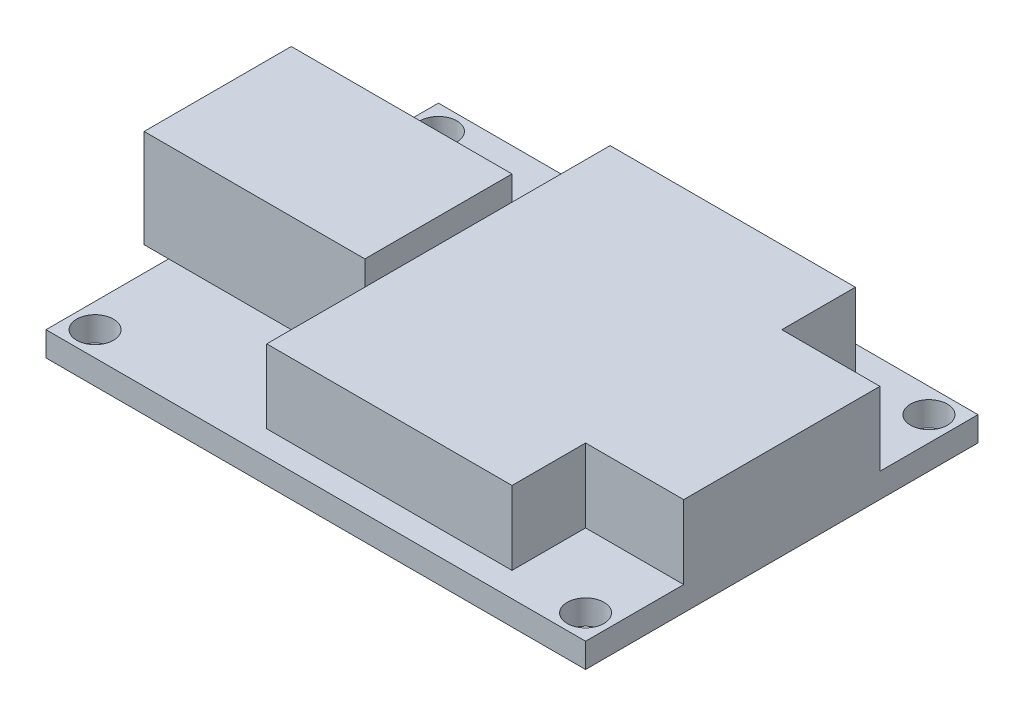
SolidWorks part; units mm, degrees
ref_plane "Front Plane" through (0, 0, 0) normal (0, 0, 1) x (1, 0, 0)
ref_plane "Top Plane" through (0, 0, 0) normal (0, 1, 0) x (1, 0, 0)
ref_plane "Right Plane" through (0, 0, 0) normal (1, 0, 0) x (0, 0, -1)
sketch "Sketch1" plane through (0, 0, 0) normal (0, 1, 0) x (1, 0, 0)
  line L1 (-17.4625, 12.7) -> (17.4625, 12.7)
  line L2 (-17.4625, 12.7) -> (-17.4625, -12.7)
  line L3 (-17.4625, -12.7) -> (17.4625, -12.7)
  line L4 (17.4625, 12.7) -> (17.4625, -12.7)
  line L5 (-17.4625, 12.7) -> (17.4625, -12.7) construction
  line L6 (-17.4625, -12.7) -> (17.4625, 12.7) construction
  point P0 (0, 0)
  dimension "D1" = 25.4
  dimension "D2" = 34.925
extrude "Boss-Extrude1" add sketch "Sketch1" along normal blind 1.5875
sketch "Sketch2" plane through (0, 1.5875, 0) normal (0, 1, 0) x (1, 0, 0)
  line L0 (17.4625, 12.7) -> (-17.4625, 12.7) construction
  line L1 (-4.7625, 11.1125) -> (11.1125, 11.1125)
  line L2 (-4.7625, 11.1125) -> (-4.7625, -11.1125)
  line L3 (-4.7625, -11.1125) -> (11.1125, -11.1125)
  line L4 (11.1125, 11.1125) -> (11.1125, 6.35)
  line L5 (-17.4625, -12.7) -> (17.4625, -12.7) construction
  line L6 (17.4625, -12.7) -> (17.4625, 12.7) construction
  line L7 (-17.4625, 12.7) -> (-17.4625, -12.7) construction
  line L8 (17.4625, 12.7) -> (-17.4625, 12.7) construction
  line L9 (11.1125, 6.35) -> (17.4625, 6.35)
  line L11 (11.1125, -6.35) -> (17.4625, -6.35)
  line L12 (17.4625, 6.35) -> (17.4625, -6.35)
  line L13 (11.1125, -6.35) -> (11.1125, -11.1125)
  dimension "D1" = 1.5875
  dimension "D2" = 1.5875
  dimension "D3" = 6.35
  dimension "D4" = 12.7
  dimension "D5" = 6.35
  dimension "D6" = 6.35
extrude "Boss-Extrude2" add sketch "Sketch2" along normal blind 4.7625
sketch "Sketch4" plane through (0, 1.5875, 0) normal (0, 1, 0) x (1, 0, 0)
  line L0 (-4.7625, 11.1125) -> (-4.7625, -11.1125) construction
  line L1 (-19.05, 4.7625) -> (-4.7625, 4.7625)
  line L2 (-19.05, 4.7625) -> (-19.05, -4.7625)
  line L3 (-19.05, -4.7625) -> (-4.7625, -4.7625)
  line L4 (-4.7625, 4.7625) -> (-4.7625, -4.7625)
  line L5 (-17.4625, 12.7) -> (-17.4625, -12.7) construction
  point P6 (-19.05, 0)
  dimension "D1" = 9.525
  dimension "D2" = 1.5875
extrude "Boss-Extrude7" add sketch "Sketch4" along normal blind 6.35
sketch "Sketch5" plane through (0, 6.35, 0) normal (0, 1, 0) x (1, 0, 0)
  line L0 (-4.7625, 0) -> (17.4625, 0) construction
  line L1 (-4.7625, 4.7625) -> (-4.7625, -4.7625) construction
  line L2 (17.4625, -6.35) -> (17.4625, 6.35) construction
  text T0 "Shield" font "Century Gothic" height 3.5
sketch "Sketch6" plane through (0, 1.5875, 0) normal (0, 1, 0) x (1, 0, 0)
  line L1 (17.4625, 12.7) -> (-17.4625, 12.7) construction
  line L2 (-17.4625, -12.7) -> (17.4625, -12.7) construction
  line L3 (17.4625, 6.35) -> (17.4625, 12.7) construction
  line L4 (-17.4625, 12.7) -> (-17.4625, 4.7625) construction
  circle A0 centre (-15.875, 11.1125) radius 1.1906
  circle A1 centre (-15.875, -11.1125) radius 1.1906
  circle A2 centre (15.875, -11.1125) radius 1.1906
  circle A3 centre (15.875, 11.1125) radius 1.1906
  dimension "D5" = 2.3812
  dimension "D1" = 1.5875
  dimension "D2" = 1.5875
  dimension "D3" = 1.5875
  dimension "D4" = 1.5875
extrude "Cut-Extrude1" cut sketch "Sketch6" against normal through all
